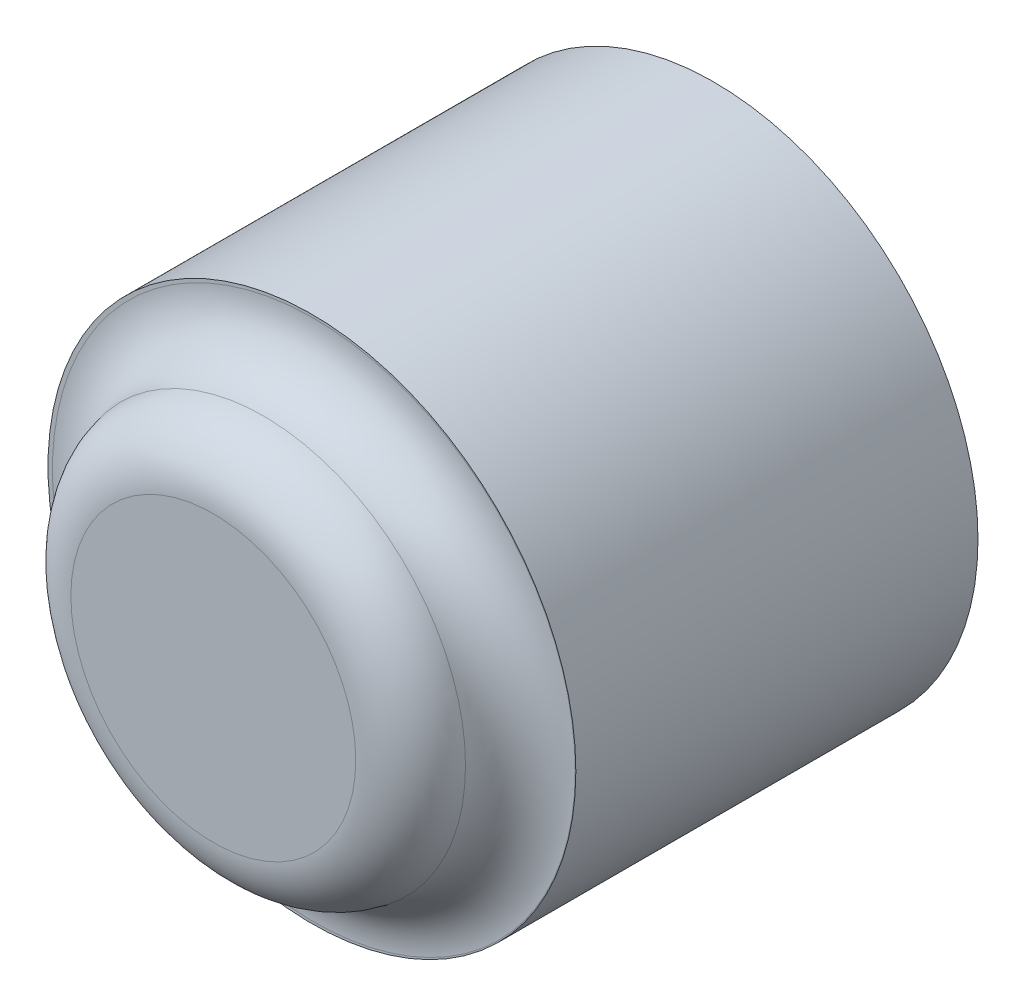
SolidWorks part; units mm, degrees
ref_plane "Front Plane" through (0, 0, 0) normal (0, 0, 1) x (1, 0, 0)
ref_plane "Top Plane" through (0, 0, 0) normal (0, 1, 0) x (1, 0, 0)
ref_plane "Right Plane" through (0, 0, 0) normal (1, 0, 0) x (0, 0, -1)
sketch "Sketch1" plane through (0, 0, 0) normal (0, 0, 1) x (1, 0, 0)
  line L0 (0, 0) -> (0, 200) construction
  circle A0 centre (0, 174.5085) radius 5.25
  dimension "D1" = 10.5
extrude "Boss-Extrude1" add sketch "Sketch1" along normal blind 8
sketch "Sketch2" plane through (0, 0, 8) normal (0, 0, 1) x (1, 0, 0)
  line L0 (0, 179.7585) -> (0.0771, 169.259) construction
  circle A0 centre (0, 174.5085) radius 5.25 construction
  circle A1 centre (0.0386, 174.5087) radius 4
  dimension "D1" = 8
extrude "Boss-Extrude2" add sketch "Sketch2" along normal blind 2
fillet "Fillet2" radius 1.2 1 edges at (4.0386, 174.5087, 8)
fillet "Fillet3" radius 1.2 1 edges at (4.0386, 174.5087, 10)
